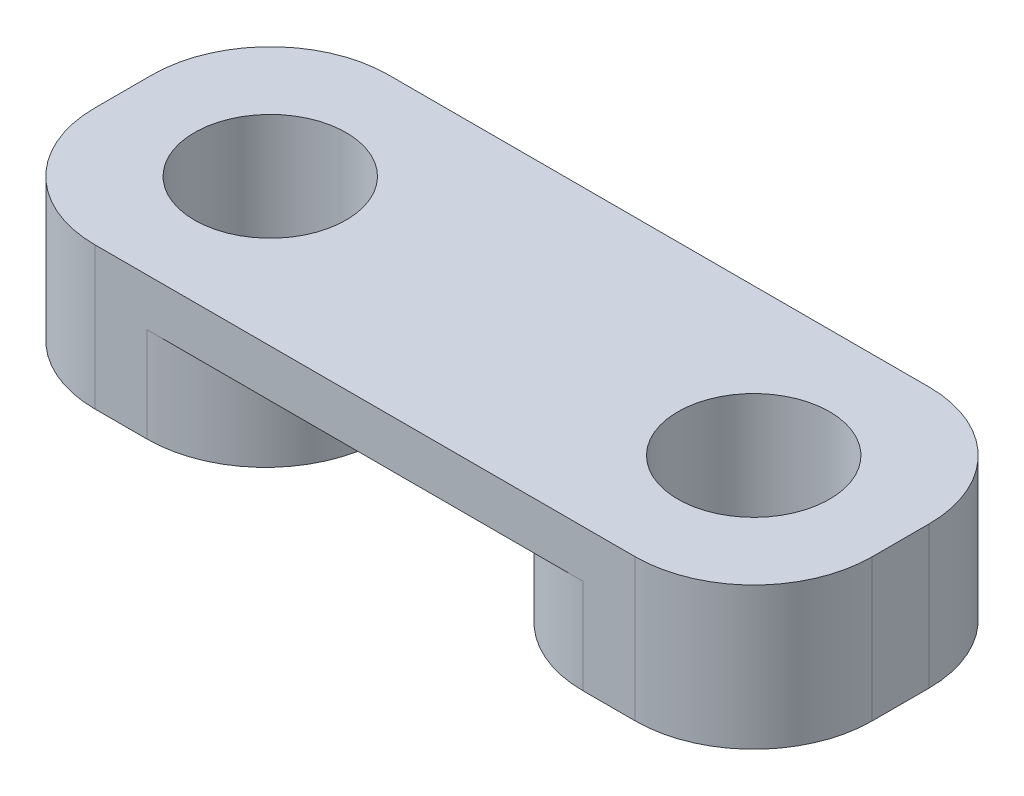
SolidWorks part; units mm, degrees
ref_plane "Front Plane" through (0, 0, 0) normal (0, 0, 1) x (1, 0, 0)
ref_plane "Top Plane" through (0, 0, 0) normal (0, 1, 0) x (1, 0, 0)
ref_plane "Right Plane" through (0, 0, 0) normal (1, 0, 0) x (0, 0, -1)
sketch "Sketch1" plane through (0, 0, 0) normal (0, 1, 0) x (1, 0, 0)
  line L0 (-8.199, 0) -> (8.199, 0)
  line L1 (8.199, 0) -> (8.199, 6.2)
  line L2 (8.199, 6.2) -> (-8.199, 6.2)
  line L3 (-8.199, 6.2) -> (-8.199, 0)
  line L4 (0, 0) -> (0, 9.4869) construction
  circle A0 centre (-5.099, 3.1) radius 1.6
  circle A1 centre (5.099, 3.1) radius 1.6
  point P3 (0, 0)
  point P12 (-8.199, 3.1)
  dimension "D1" = 3.2
  dimension "D2" = 6.2
  dimension "D3" = 5.099
  dimension "D4" = 16.398
extrude "Boss-Extrude1" add sketch "Sketch1" along normal blind 3
sketch "Sketch5" plane through (0, 0, 0) normal (0, 0, 1) x (1, 0, 0)
  line L0 (-2.099, 0) -> (-2.099, 2)
  line L1 (-8.199, 0) -> (8.199, 0) construction
  line L2 (-2.099, 2) -> (2.099, 2)
  line L3 (2.099, 2) -> (2.099, 0)
  line L4 (-8.199, 3) -> (8.199, 3) construction
  line L8 (-2.099, 0) -> (2.099, 0)
  point P8 (0, 0)
  dimension "D1" = 1
  dimension "D2" = 4.198
extrude "Cut-Extrude4" cut sketch "Sketch5" against normal through all
fillet "Fillet2" radius 2.5 8 edges at (8.199, 1.5, -6.2) (8.199, 1.5, 0) (-8.199, 1.5, -6.2) (-8.199, 1.5, 0) (2.099, 1, 0) (2.099, 1, -6.2) (-2.099, 1, -6.2) (-2.099, 1, 0)
equation "\"D3@Sketch1\"=10.198039/2"
